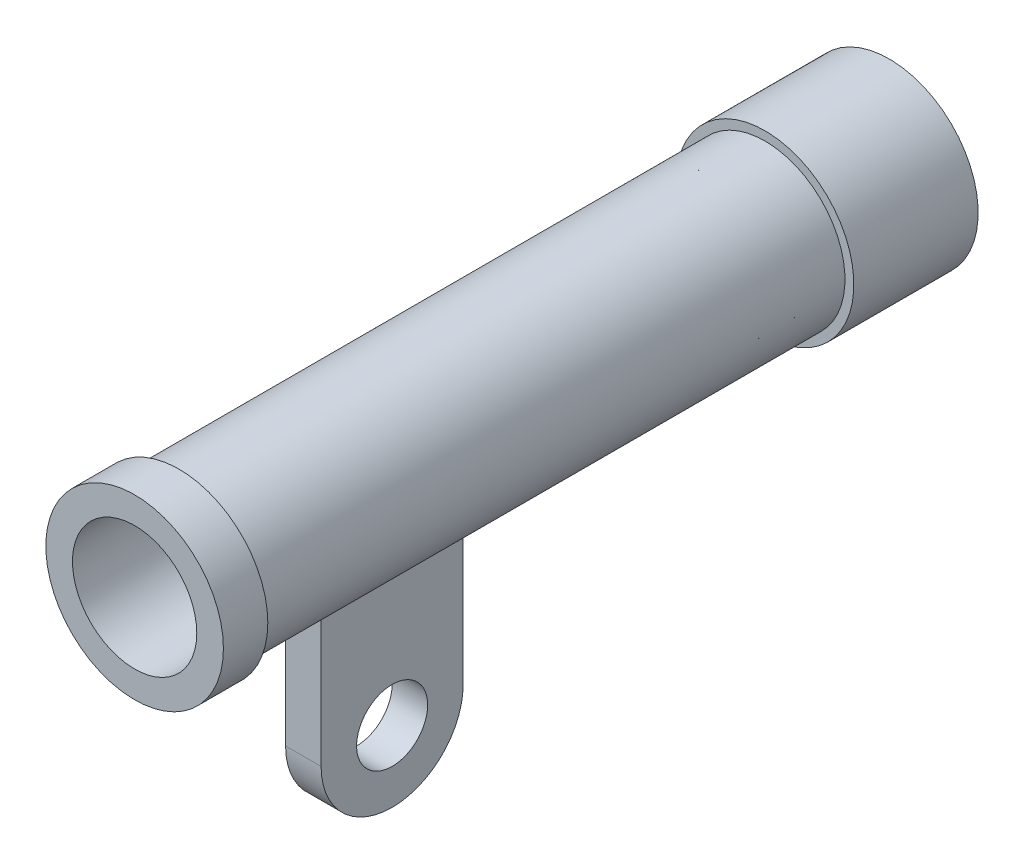
SolidWorks part; units mm, degrees
material "AISI 1020"
ref_plane "Ön Düzlem" through (0, 0, 0) normal (0, 0, 1) x (1, 0, 0)
ref_plane "Üst Düzlem" through (0, 0, 0) normal (0, 1, 0) x (1, 0, 0)
ref_plane "Sağ Düzlem" through (0, 0, 0) normal (1, 0, 0) x (0, 0, -1)
sketch "Çizim1" plane through (0, 0, 0) normal (0, 0, 1) x (1, 0, 0)
  circle A0 centre (0, 0) radius 45
  dimension "D1" = 90
extrude "Yükseklik-Ekstrüzyon1" add sketch "Çizim1" along normal blind 400
sketch "Çizim2" plane through (0, 0, 400) normal (0, 0, 1) x (1, 0, 0)
  circle A0 centre (0, 0) radius 35
  dimension "D1" = 70
extrude "Kes-Ekstrüzyon1" cut sketch "Çizim2" against normal blind 350
sketch "Çizim4" plane through (0, 0, 0) normal (0, 0, -1) x (-1, 0, 0)
  circle A0 centre (0, 0) radius 50
  dimension "D1" = 100
extrude "Yükseklik-Ekstrüzyon2" add sketch "Çizim4" against normal blind 70
sketch "Çizim5" plane through (0, 0, 0) normal (1, 0, 0) x (0, 0, -1)
  line L0 (-330, -45) -> (-330, -125)
  line L1 (-400, -45) -> (-70, -45) construction
  line L2 (-250, -125) -> (-250, -45)
  line L3 (-330, -45) -> (-250, -45)
  line L4 (-400, 45) -> (-400, -45) construction
  arc A0 (-330, -125) -> (-250, -125) centre (-290, -125) ccw
  circle A1 centre (-290, -125) radius 20
  dimension "D1" = 40
  dimension "D3" = 40
  dimension "D2" = 80
  dimension "D4" = 70
sketch "Çizim6" plane through (0, 0, 400) normal (0, 0, 1) x (1, 0, 0)
  circle A0 centre (0, 0) radius 50
  circle A1 centre (0, 0) radius 35 construction
  circle A2 centre (0, 0) radius 35
  dimension "D1" = 100
extrude "Yükseklik-Ekstrüzyon4" add sketch "Çizim6" along normal blind 25
extrude "Yükseklik-Ekstrüzyon5" add sketch "Çizim5" along normal mid plane 20 separate body
